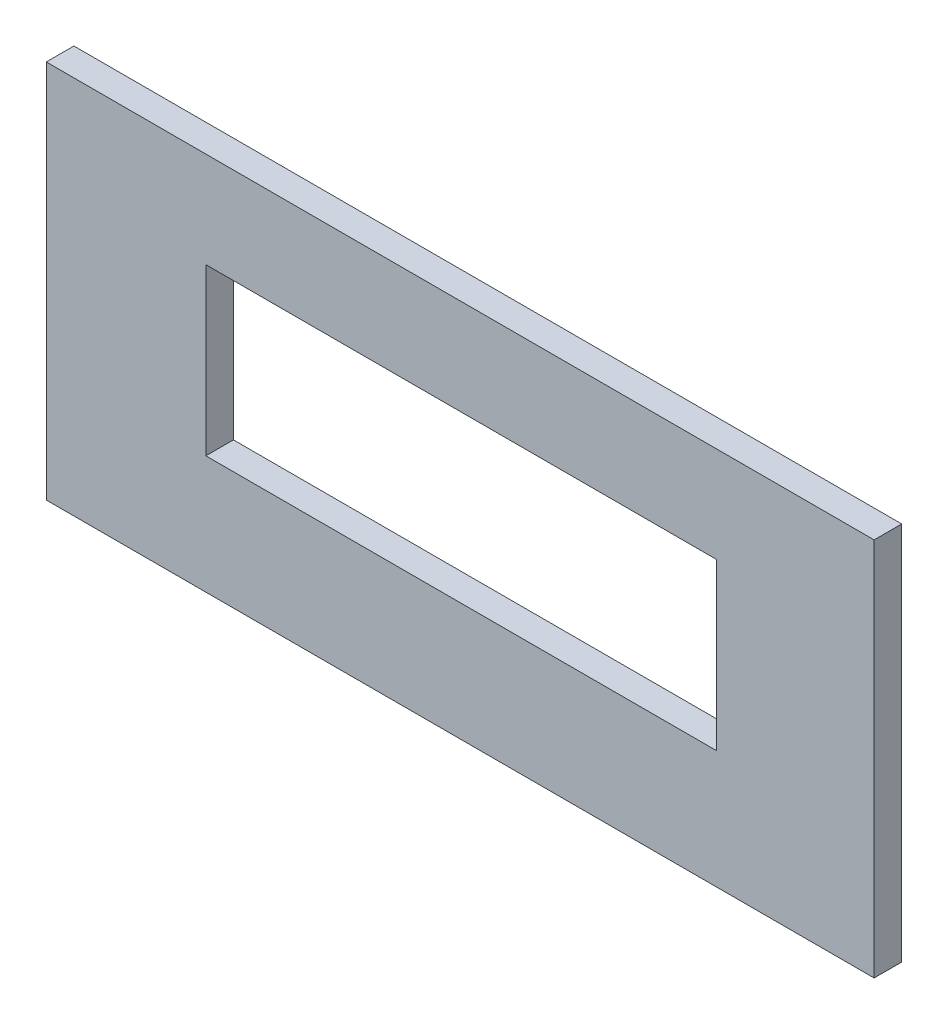
SolidWorks part; units mm, degrees
ref_plane "Plan de face" through (0, 0, 0) normal (0, 0, 1) x (1, 0, 0)
ref_plane "Plan de dessus" through (0, 0, 0) normal (0, 1, 0) x (1, 0, 0)
ref_plane "Plan de droite" through (0, 0, 0) normal (1, 0, 0) x (0, 0, -1)
sketch "Esquisse1" plane through (0, 0, 0) normal (0, 0, 1) x (1, 0, 0)
  line L1 (0, 0) -> (-120, 0)
  line L2 (0, 0) -> (0, -55)
  line L3 (0, -55) -> (-120, -55)
  line L4 (-120, 0) -> (-120, -55)
  dimension "D1" = 120
  dimension "D2" = 55
extrude "Boss.-Extru.1" add sketch "Esquisse1" along normal blind 4
sketch "Esquisse3" plane through (0, 0, 4) normal (0, 0, 1) x (1, 0, 0)
  line L1 (-96.8707, -13.8836) -> (-22.8707, -13.8836)
  line L2 (-96.8707, -13.8836) -> (-96.8707, -37.8836)
  line L3 (-96.8707, -37.8836) -> (-22.8707, -37.8836)
  line L4 (-22.8707, -13.8836) -> (-22.8707, -37.8836)
  line L5 (-96.8707, -13.8836) -> (-22.8707, -37.8836) construction
  line L6 (-96.8707, -37.8836) -> (-22.8707, -13.8836) construction
  point P0 (-59.8707, -25.8836)
  point P5 (-59.8707, -25.8836)
  dimension "D1" = 74
  dimension "D2" = 24
extrude "Enlèv. mat.-Extru.1" cut sketch "Esquisse3" against normal blind 4
